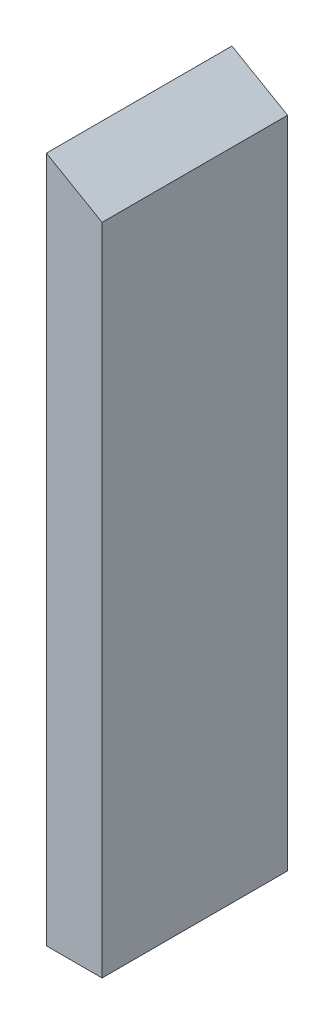
SolidWorks part; units mm, degrees
ref_plane "Front Plane" through (0, 0, 0) normal (0, 0, 1) x (1, 0, 0)
ref_plane "Top Plane" through (0, 0, 0) normal (0, 1, 0) x (1, 0, 0)
ref_plane "Right Plane" through (0, 0, 0) normal (1, 0, 0) x (0, 0, -1)
sketch "Sketch1" plane through (0, 0, 0) normal (0, 0, 1) x (1, 0, 0)
  line L0 (-19.4361, 59.5794) -> (-16.4361, 57.8473)
  line L2 (-19.4361, 59.5794) -> (-19.4361, 22.5794)
  line L3 (-19.4361, 22.5794) -> (-16.4361, 22.5794)
  line L4 (-16.4361, 57.8473) -> (-16.4361, 22.5794)
  dimension "D1" = 37
  dimension "D2" = 3
  dimension "D3" = 60
extrude "Boss-Extrude1" add sketch "Sketch1" along normal blind 10
